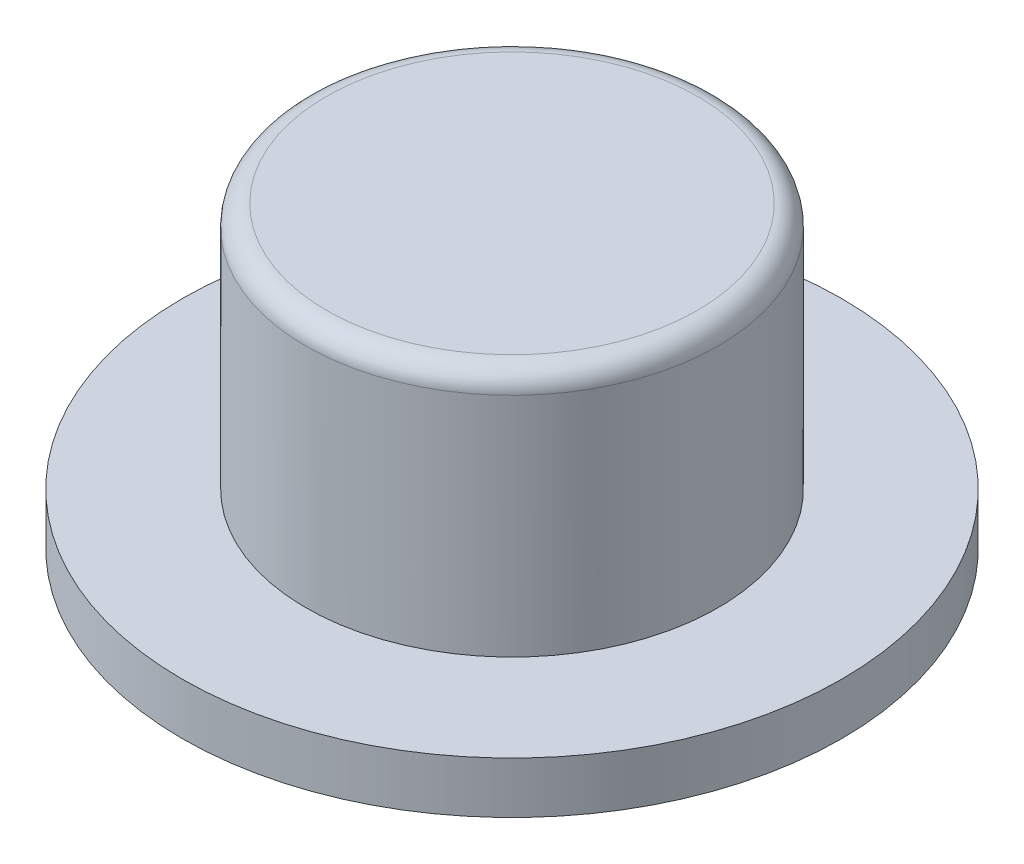
SolidWorks part; units mm, degrees
ref_plane "Front Plane" through (0, 0, 0) normal (0, 0, 1) x (1, 0, 0)
ref_plane "Top Plane" through (0, 0, 0) normal (0, 1, 0) x (1, 0, 0)
ref_plane "Right Plane" through (0, 0, 0) normal (1, 0, 0) x (0, 0, -1)
sketch "Sketch1" plane through (0, 0, 0) normal (0, 0, 1) x (1, 0, 0)
  line L1 (0, 7.25) -> (5, 7.25)
  line L2 (5, 7.25) -> (5, 1.25)
  line L3 (5, 1.25) -> (8, 1.25)
  line L4 (8, 1.25) -> (8, 0)
  line L6 (0, 7.25) -> (0, 6.9292) construction
  line L7 (0, 7.25) -> (0, 0)
  line L10 (0, 0) -> (8, 0)
  dimension "D1" = 5
  dimension "D2" = 3
  dimension "D3" = 6
  dimension "D4" = 1.25
revolve "Revolve1" add sketch "Sketch1" angle 360 about L6
sketch "Sketch2" plane through (0, 0, 0) normal (0, -1, 0) x (1, 0, 0)
  line L1 (-1.25, -1.75) -> (1.25, -1.75)
  line L2 (-1.25, -1.75) -> (-1.25, 1.75)
  line L3 (-1.25, 1.75) -> (1.25, 1.75)
  line L4 (1.25, -1.75) -> (1.25, 1.75)
  line L5 (-1.25, -1.75) -> (1.25, 1.75) construction
  line L6 (-1.25, 1.75) -> (1.25, -1.75) construction
  point P0 (0, 0)
  dimension "D1" = 2.5
  dimension "D2" = 3.5
extrude "Cut-Extrude1" cut sketch "Sketch2" against normal blind 3.5 contours L3 L4 L1 L2
fillet "Fillet1" radius 0.5 1 edges at (-5, 7.25, 0)
